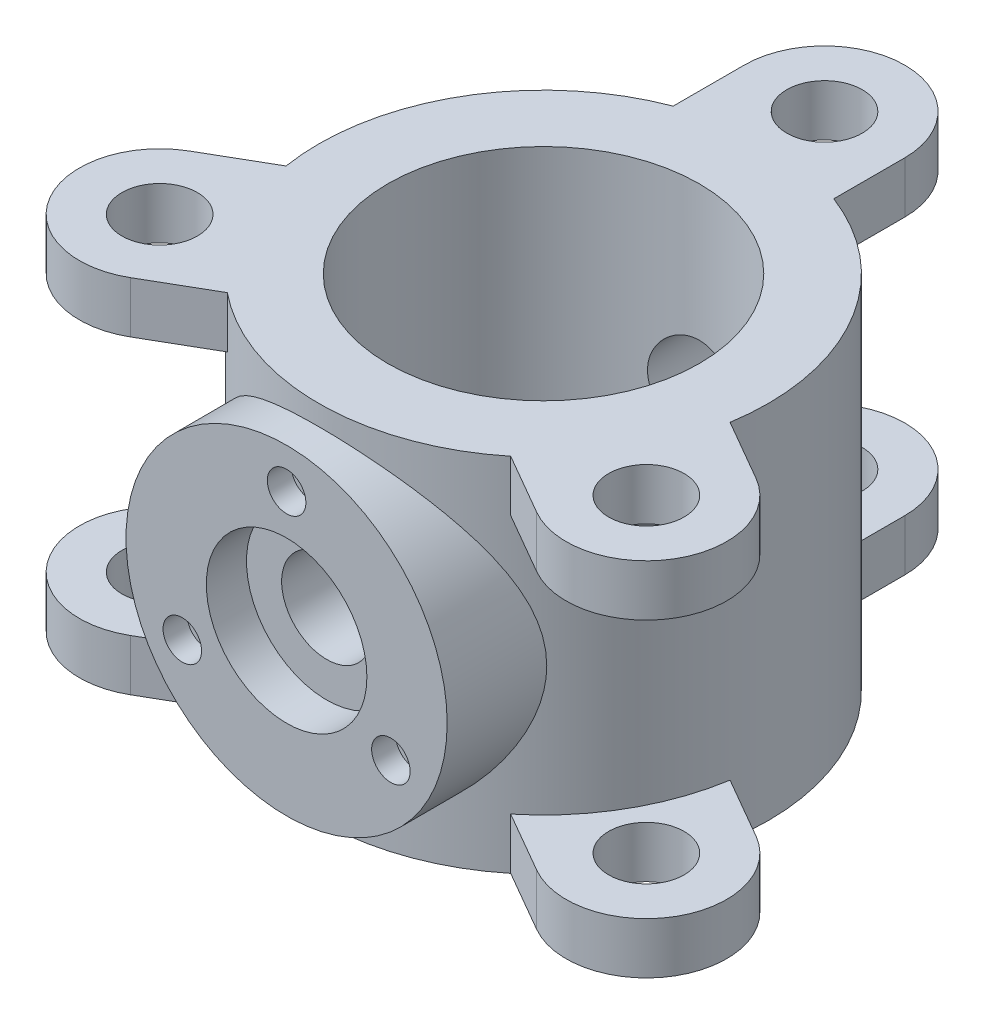
SolidWorks part; units mm, degrees
ref_plane "Front Plane" through (0, 0, 0) normal (0, 0, 1) x (1, 0, 0)
ref_plane "Top Plane" through (0, 0, 0) normal (0, 1, 0) x (1, 0, 0)
ref_plane "Right Plane" through (0, 0, 0) normal (1, 0, 0) x (0, 0, -1)
sketch "Sketch1" plane through (0, 0, 0) normal (0, 1, 0) x (1, 0, 0)
  circle A0 centre (0, 0) radius 97
  circle A1 centre (0, 0) radius 140
  dimension "D1" = 194
  dimension "D2" = 280
extrude "Boss-Extrude1" add sketch "Sketch1" along normal blind 225
sketch "Sketch2" plane through (0, 225, 0) normal (0, 1, 0) x (1, 0, 0)
  line L0 (0, 199.8878) -> (0, 151.5) construction
  line L1 (-363.2153, 0) -> (346.8031, 0) construction
  line L2 (0, 99.4331) -> (0, -203.589) construction
  line L3 (-23.5, 175) -> (23.5, 175) construction
  line L4 (-50, 175) -> (-50, 99.4331)
  line L5 (-50, 99.4331) -> (50, 99.4331)
  line L6 (50, 175) -> (50, 99.4331)
  circle A1 centre (0, 175) radius 23.5
  arc A2 (50, 175) -> (-50, 175) centre (0, 175) ccw
  point P5 (0, 137.2165)
  dimension "D3" = 47
  dimension "D2" = 175
extrude "Boss-Extrude7" add sketch "Sketch2" against normal blind 32
pattern_circular "CirPattern1" count 3 over 360 about axis through (0, 0, 0) along (0, 1, 0) of "Boss-Extrude7"
ref_plane "Plane1" through (0, 112.5, 0) normal (0, 1, 0) x (1, 0, 0)
mirror "Mirror1" about plane through (0, 112.5, 0) normal (0, 1, 0) of "CirPattern1", "Boss-Extrude7"
ref_plane "Plane3" through (0, 0, 160) normal (0, 0, 1) x (1, 0, 0)
sketch "Sketch3" plane through (0, 0, 160) normal (0, 0, 1) x (1, 0, 0)
  line L0 (0, 296.2189) -> (0, -71.2189) construction
  line L1 (-88.2475, 0) -> (88.2475, 0) construction
  circle A0 centre (0, 112.5) radius 100
  point P5 (0, 0)
  dimension "D1" = 200
  dimension "D2" = 112.5
extrude "Boss-Extrude8" add sketch "Sketch3" against normal up to next
sketch "Sketch4" plane through (0, 0, 160) normal (0, 0, 1) x (1, 0, 0)
  circle A0 centre (0, 112.5) radius 50
  dimension "D1" = 100
extrude "Cut-Extrude1" cut sketch "Sketch4" against normal blind 25
sketch "Sketch5" plane through (0, 0, 160) normal (0, 0, 1) x (1, 0, 0)
  circle A0 centre (0, 112.5) radius 28.1
  dimension "D1" = 56.2
extrude "Cut-Extrude2" cut sketch "Sketch5" against normal through all
sketch "Sketch6" plane through (0, 0, 160) normal (0, 0, 1) x (1, 0, 0)
  line L0 (0, 278.7645) -> (0, -64.0581) construction
  circle A0 centre (0, 187.5) radius 12
  circle A1 centre (0, 112.5) radius 50 construction
  point P5 (0, 0)
  dimension "D1" = 24
  dimension "D2" = 75
extrude "Cut-Extrude3" cut sketch "Sketch6" against normal blind 15
pattern_circular "CirPattern2" count 3 over 360 about axis through (0, 112.5, 0) along (0, 0, 1) of "Cut-Extrude3"
